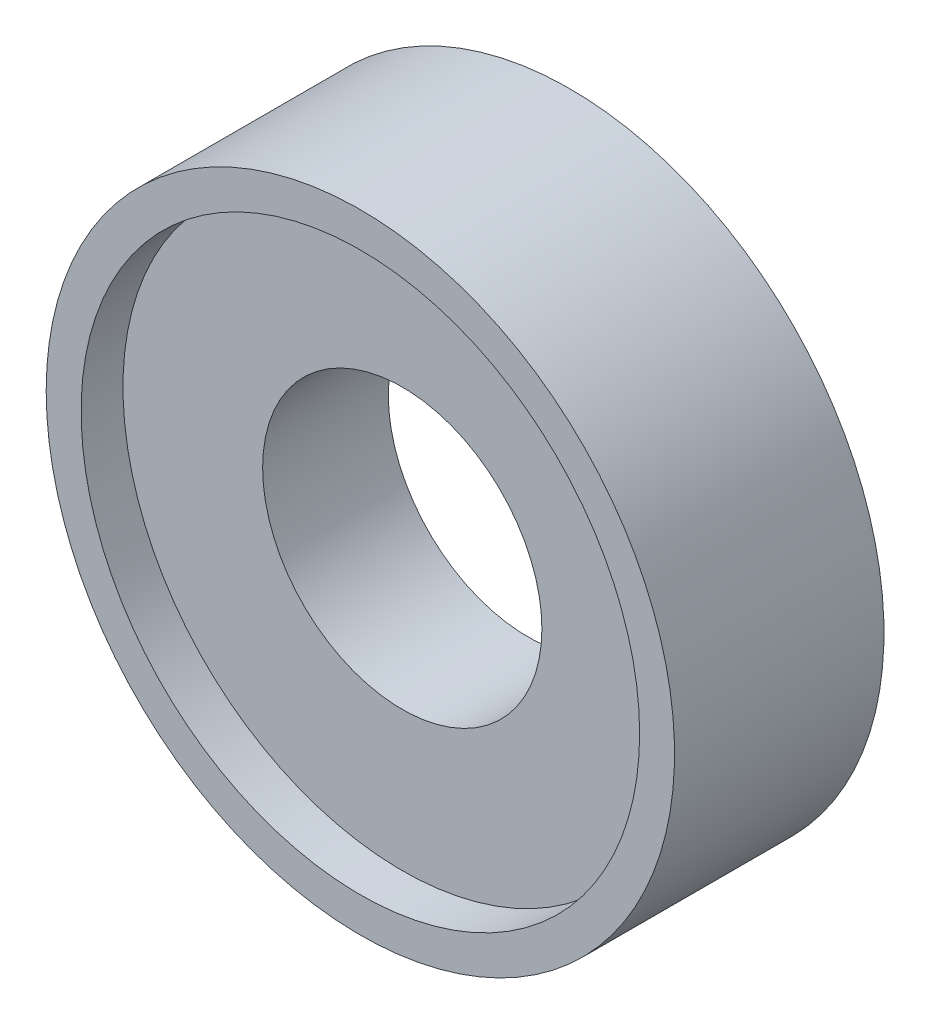
SolidWorks part; units mm, degrees
material "1060 Alloy"
ref_plane "Front Plane" through (0, 0, 0) normal (0, 0, 1) x (1, 0, 0)
ref_plane "Top Plane" through (0, 0, 0) normal (0, 1, 0) x (1, 0, 0)
ref_plane "Right Plane" through (0, 0, 0) normal (1, 0, 0) x (0, 0, -1)
sketch "Sketch1" plane through (0, 0, 0) normal (0, 0, 1) x (1, 0, 0)
  circle A0 centre (0, 0) radius 57.15
  dimension "D1" = 114.3
extrude "Boss-Extrude1" add sketch "Sketch1" along normal blind 38.1
sketch "Sketch2" plane through (0, 0, 38.1) normal (0, 0, 1) x (1, 0, 0)
  circle A0 centre (0, 0) radius 25.4
extrude "Cut-Extrude1" cut sketch "Sketch2" against normal blind 38.1 contours A0
sketch "Sketch3" plane through (0, 0, 38.1) normal (0, 0, 1) x (1, 0, 0)
  circle A0 centre (0, 0) radius 50.8
  dimension "D1" = 101.6
extrude "Cut-Extrude2" cut sketch "Sketch3" against normal blind 7.62
sketch "Sketch5" plane through (0, 0, 0) normal (0, 0, -1) x (-1, 0, 0)
  circle A0 centre (0, 0) radius 50.8
extrude "Cut-Extrude3" cut sketch "Sketch5" against normal blind 7.62
